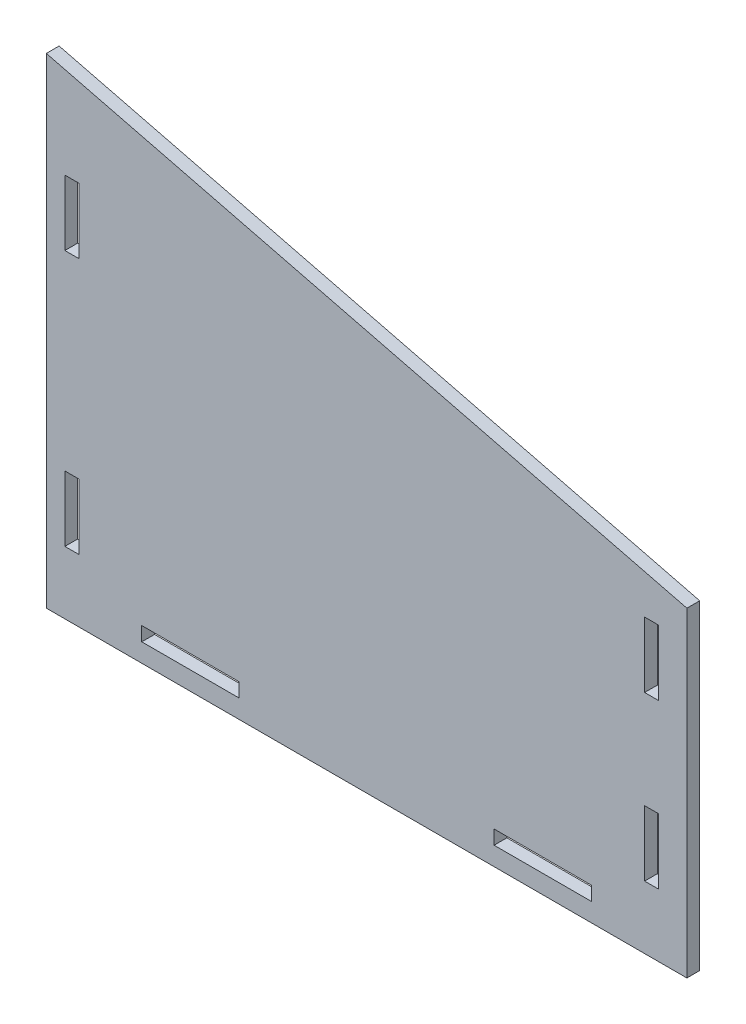
SolidWorks part; units mm, degrees
ref_plane "Спереди" through (0, 0, 0) normal (0, 0, 1) x (1, 0, 0)
ref_plane "Сверху" through (0, 0, 0) normal (0, 1, 0) x (1, 0, 0)
ref_plane "Справа" through (0, 0, 0) normal (1, 0, 0) x (0, 0, -1)
sketch "Эскиз1" plane through (0, 0, 0) normal (0, 0, 1) x (1, 0, 0)
  line L0 (0, 0) -> (0, 150)
  line L1 (0, 0) -> (200, 0)
  line L2 (200, 0) -> (200, 100)
  line L3 (200, 100) -> (0, 150)
  line L4 (100, 0) -> (100, 42.511) construction
  line L5 (186.8, 40) -> (191.2, 40)
  line L6 (186.8, 40) -> (186.8, 19.6)
  line L7 (186.8, 19.6) -> (191.2, 19.6)
  line L8 (191.2, 40) -> (191.2, 19.6)
  line L13 (200, 50) -> (159.4478, 50) construction
  line L14 (0, 75) -> (18.3539, 75) construction
  line L16 (139.8, 10.2) -> (170.2, 10.2)
  line L17 (139.8, 10.2) -> (139.8, 5.8)
  line L18 (139.8, 5.8) -> (170.2, 5.8)
  line L19 (170.2, 10.2) -> (170.2, 5.8)
  line L23 (60.2, 5.8) -> (29.8, 5.8)
  line L24 (29.8, 10.2) -> (29.8, 5.8)
  line L25 (60.2, 10.2) -> (29.8, 10.2)
  line L26 (60.2, 10.2) -> (60.2, 5.8)
  line L31 (8, 40) -> (8, 99.6) construction
  line L32 (5.8, 99.6) -> (10.2, 99.6)
  line L33 (5.8, 99.6) -> (5.8, 120)
  line L34 (5.8, 120) -> (10.2, 120)
  line L35 (10.2, 99.6) -> (10.2, 120)
  line L36 (155, 10.2) -> (155, 5.8) construction
  line L37 (45, 10.2) -> (45, 5.8) construction
  line L39 (5.8, 109.8) -> (10.2, 109.8) construction
  line L40 (186.8, 40) -> (186.8, 70.6) construction
  line L41 (186.8, 70.6) -> (191.2, 70.6)
  line L42 (186.8, 70.6) -> (186.8, 91)
  line L43 (186.8, 91) -> (191.2, 91)
  line L44 (191.2, 70.6) -> (191.2, 91)
  line L45 (191.2, 40) -> (191.2, 70.6) construction
  line L46 (186.8, 80.8) -> (191.2, 80.8) construction
  line L47 (186.8, 29.8) -> (191.2, 29.8) construction
  line L48 (189, 19.6) -> (189, 11.2014) construction
  line L49 (139.8, 8) -> (170.2, 8) construction
  line L50 (8, 40) -> (8, 19.6) construction
  line L51 (5.8, 40) -> (10.2, 40)
  line L52 (5.8, 40) -> (5.8, 19.6)
  line L53 (5.8, 19.6) -> (10.2, 19.6)
  line L54 (10.2, 40) -> (10.2, 19.6)
  line L55 (5.8, 29.8) -> (10.2, 29.8) construction
  dimension "D1" = 150
  dimension "D2" = 100
  dimension "D3" = 200
  dimension "D4" = 4.4
  dimension "D5" = 20.4
  dimension "D6" = 20
  dimension "D7" = 11
  dimension "D8" = 8
  dimension "D9" = 30.4
  dimension "D10" = 110
  dimension "D11" = 4.4
  dimension "D12" = 4.4
  dimension "D13" = 20.4
  dimension "D14" = 8
  dimension "D15" = 51
  dimension "D16" = 20.4
  dimension "D17" = 20.4
  dimension "D18" = 4.4
  dimension "D19" = 80
  dimension "D20" = 109.8
extrude "Бобышка-Вытянуть1" add sketch "Эскиз1" along normal blind 4
